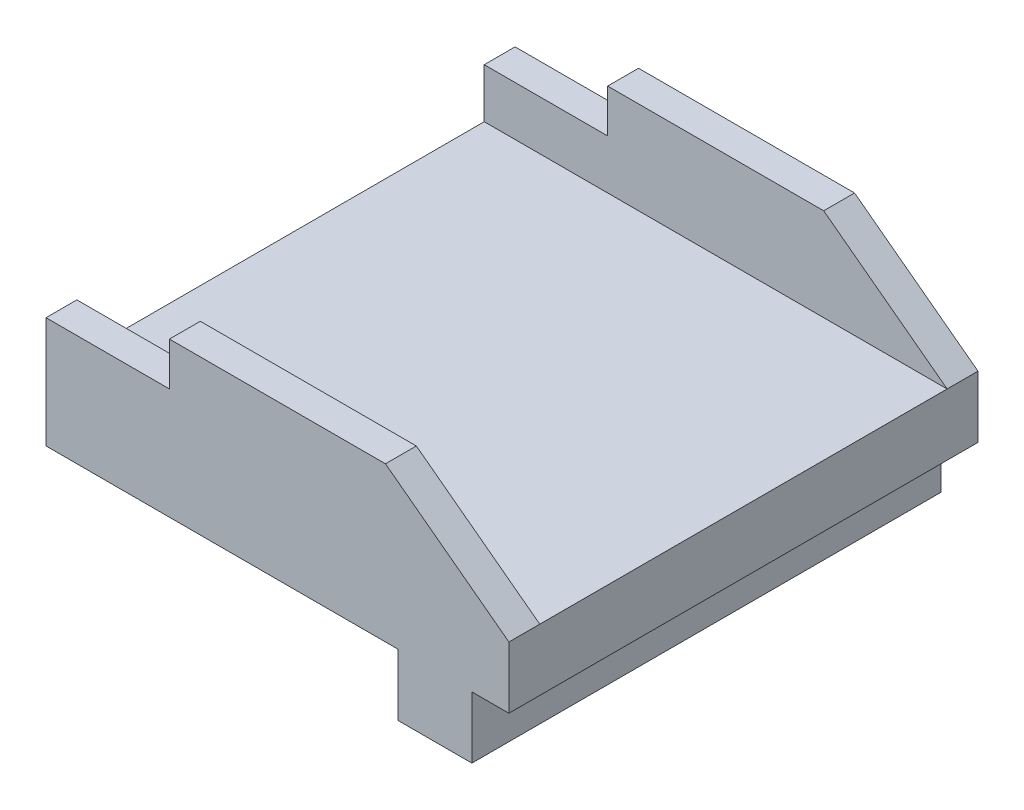
SolidWorks part; units mm, degrees
ref_plane "Спереди" through (0, 0, 0) normal (0, 0, 1) x (1, 0, 0)
ref_plane "Сверху" through (0, 0, 0) normal (0, 1, 0) x (1, 0, 0)
ref_plane "Справа" through (0, 0, 0) normal (1, 0, 0) x (0, 0, -1)
sketch "Эскиз1" plane through (0, 0, 0) normal (0, 0, 1) x (1, 0, 0)
  line L0 (17.5, 17.5) -> (37.5, 2.5)
  line L1 (-37.5, -17.5) -> (37.5, -17.5)
  line L2 (-37.5, -17.5) -> (-37.5, 17.5)
  line L3 (-37.5, 17.5) -> (37.5, 17.5)
  line L4 (37.5, -17.5) -> (37.5, 17.5)
  line L5 (-37.5, -17.5) -> (37.5, 17.5) construction
  line L6 (-37.5, 17.5) -> (37.5, -17.5) construction
  line L7 (-37.5, 17.5) -> (-17.5, 17.5)
  line L8 (-37.5, 17.5) -> (-37.5, 10.5)
  line L9 (-37.5, 10.5) -> (-17.5, 10.5)
  line L10 (-17.5, 17.5) -> (-17.5, 10.5)
  line L11 (-37.5, -17.5) -> (19.5, -17.5)
  line L12 (-37.5, -17.5) -> (-37.5, -7.5)
  line L13 (-37.5, -7.5) -> (19.5, -7.5)
  line L14 (19.5, -17.5) -> (19.5, -7.5)
  line L15 (37.5, -17.5) -> (31.5, -17.5)
  line L16 (37.5, -17.5) -> (37.5, -7.5)
  line L17 (37.5, -7.5) -> (31.5, -7.5)
  line L18 (31.5, -17.5) -> (31.5, -7.5)
  point P0 (0, 0)
  dimension "D1" = 75
  dimension "D2" = 35
  dimension "D3" = 6
  dimension "D4" = 12
  dimension "D5" = 10
  dimension "D6" = 20
  dimension "D7" = 7
  dimension "D8" = 10
  dimension "D9" = 20
extrude "Бобышка-Вытянуть1" add sketch "Эскиз1" along normal blind 76 contours L1 L18 L17 L4 L0 L3 L10 L9 L2 L13 L14
sketch "Эскиз2" plane through (37.5, 0, 0) normal (1, 0, 0) x (0, 0, -1)
  line L0 (-38, 17.5) -> (-38, -17.5) construction
  line L1 (-76, 17.5) -> (0, 17.5) construction
  line L2 (-76, -17.5) -> (0, -17.5) construction
  line L3 (-76, 2.5) -> (0, 2.5) construction
  line L4 (-71, 2.5) -> (-5, 2.5)
  line L5 (-71, 2.5) -> (-71, 17.5)
  line L6 (-71, 17.5) -> (-5, 17.5)
  line L7 (-5, 2.5) -> (-5, 17.5)
  line L8 (-71, 2.5) -> (-5, 17.5) construction
  line L9 (-71, 17.5) -> (-5, 2.5) construction
  line L10 (0, 17.5) -> (0, 2.5) construction
  point P6 (-38, 10)
  dimension "D1" = 5
extrude "Вырез-Вытянуть1" cut sketch "Эскиз2" against normal through all
